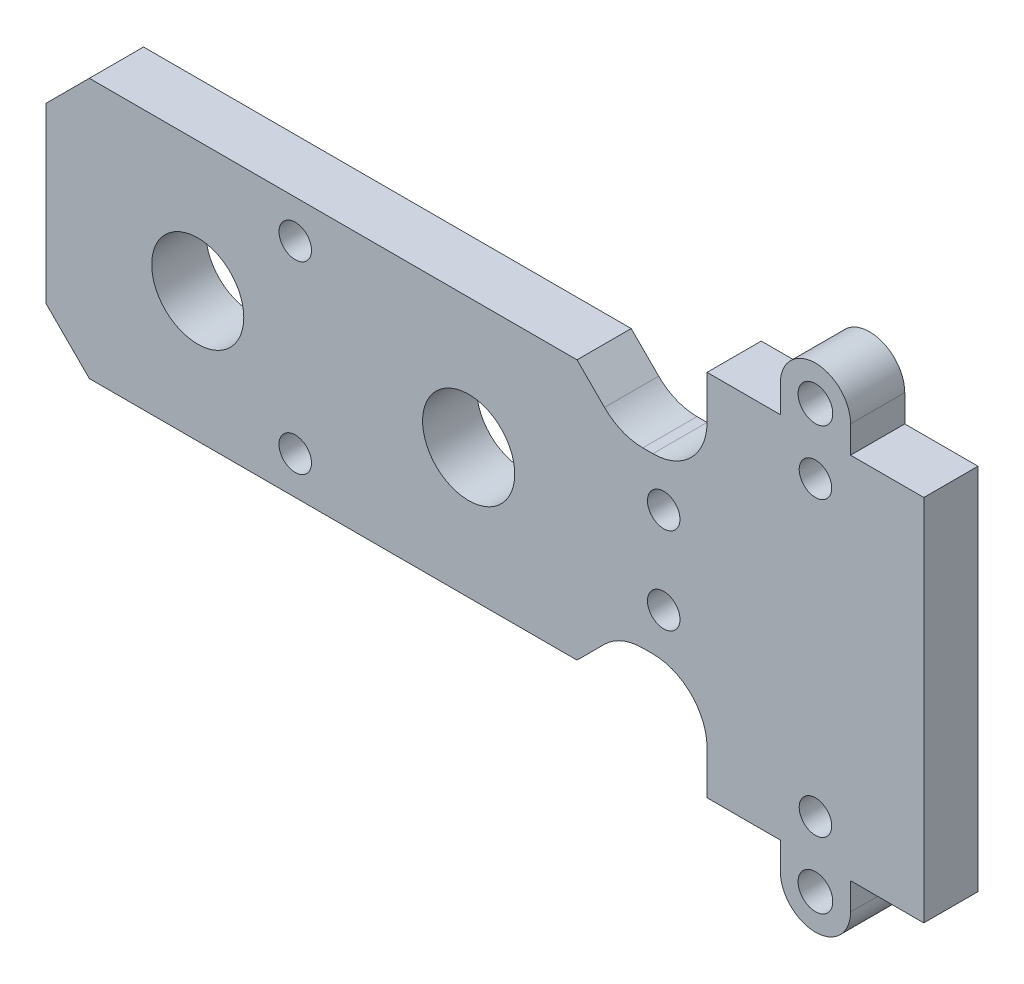
SolidWorks part; units mm, degrees
ref_plane "Plan de face" through (0, 0, 0) normal (0, 0, 1) x (1, 0, 0)
ref_plane "Plan de dessus" through (0, 0, 0) normal (0, 1, 0) x (1, 0, 0)
ref_plane "Plan de droite" through (0, 0, 0) normal (1, 0, 0) x (0, 0, -1)
sketch "Esquisse1" plane through (0, 0, 0) normal (0, 0, 1) x (1, 0, 0)
  line L0 (30.5, 0) -> (30.5, 3)
  line L1 (25.5, 8) -> (22.5, 8)
  line L2 (22.5, 8) -> (18.5, 12)
  line L3 (18.5, 12) -> (-26.5, 12)
  line L4 (-26.5, 12) -> (-30.5, 8)
  line L5 (-30.5, 8) -> (-30.5, 0)
  line L6 (22.5, -8) -> (25.5, -8)
  line L7 (30.5, -3) -> (30.5, 0)
  line L8 (-30.5, 0) -> (-30.5, -8)
  line L9 (-30.5, -8) -> (-26.5, -12)
  line L10 (-26.5, -12) -> (18.5, -12)
  line L11 (18.5, -12) -> (22.5, -8)
  arc A0 (30.5, 3) -> (25.5, 8) centre (25.5, 3) ccw
  arc A1 (25.5, -8) -> (30.5, -3) centre (25.5, -3) ccw
  circle A2 centre (-16.5, 0) radius 4.25
  circle A3 centre (-7.5, -8.5) radius 1.5
  circle A4 centre (8.5, 0) radius 4.25
  circle A5 centre (-7.5, 8.5) radius 1.5
  circle A6 centre (26.5, 4) radius 1.5
  circle A7 centre (26.5, -4) radius 1.5
extrude "Boss.-Extru.1" add sketch "Esquisse1" along normal blind 5
sketch "Esquisse2" plane through (0, 0, 0) normal (0, 0, -1) x (-1, 0, 0)
  line L0 (-30.5, -3) -> (-30.5, 3) construction
  line L2 (-30.5, 17) -> (-30.5, 8)
  line L4 (-50.5, 17) -> (-50.5, -17)
  line L5 (-30.5, -3) -> (-30.5, 3)
  line L8 (-25.5, 8) -> (-30.5, 8)
  line L10 (-30.5, -8) -> (-25.5, -8)
  line L13 (-30.5, -8) -> (-30.5, -16)
  line L19 (-30.5, 17) -> (-36.2574, 17)
  line L21 (-36.2574, 21) -> (-36.2574, 17)
  line L22 (-44.7426, 21) -> (-44.7426, 17)
  line L23 (-36.2574, -21) -> (-36.2574, -17)
  line L24 (-44.7426, -21) -> (-44.7426, -17)
  line L25 (-44.7426, 17) -> (-50.5, 17)
  line L26 (-44.7426, -17) -> (-50.5, -17)
  line L27 (-36.2574, -17) -> (-30.5, -17)
  line L28 (-30.5, -17) -> (-30.5, -16)
  circle A0 centre (-40.5, 13.5) radius 1.5
  circle A1 centre (-40.5, -13.5) radius 1.5
  circle A2 centre (-40.5, 19.5) radius 1.6
  circle A3 centre (-40.5, -19.5) radius 1.6
  arc A4 (-36.2574, 21) -> (-44.7426, 21) centre (-40.5, 19.5) ccw
  arc A5 (-44.7426, -21) -> (-36.2574, -21) centre (-40.5, -19.5) ccw
  arc A6 (-30.5, -3) -> (-25.5, -8) centre (-25.5, -3) ccw construction
  arc A7 (-25.5, 8) -> (-30.5, 3) centre (-25.5, 3) ccw construction
  arc A8 (-30.5, -3) -> (-25.5, -8) centre (-25.5, -3) ccw
  arc A9 (-25.5, 8) -> (-30.5, 3) centre (-25.5, 3) ccw
  dimension "D2" = 3
  dimension "D3" = 3
  dimension "D4" = 27
  dimension "D7" = 10
  dimension "D10" = 3.2
  dimension "D11" = 3.2
  dimension "D14" = 9
  dimension "D15" = 9
  dimension "D13" = 2.5
  dimension "D5" = 3.2
  dimension "D6" = 10
  dimension "D17" = 4
  dimension "D18" = 4
extrude "Boss.-Extru.2" add sketch "Esquisse2" against normal blind 5
fillet "Congé1" radius 1 1 edges at (44.7426, -21, 2.5)
sketch "Esquisse5" plane through (0, 0, 5) normal (0, 0, 1) x (1, 0, 0)
  line L0 (37.2574, 17) -> (37.2574, 19.5)
  line L2 (43.7426, -19.5) -> (43.7426, -17)
  line L3 (44.7426, -17) -> (44.7426, -20.8173) construction
  line L5 (37.2574, -31.95) -> (43.7426, -31.95)
  line L9 (37.2574, -17) -> (34.8491, -17)
  line L10 (36.2574, -17) -> (30.5, -17) construction
  line L11 (34.8491, -17) -> (37.2574, -31.95)
  line L12 (43.7426, -17) -> (44.7426, -17)
  line L13 (44.7426, -17) -> (44.7426, -31.95)
  line L14 (44.7426, -31.95) -> (43.7426, -31.95)
  line L15 (36.2574, 17) -> (37.2574, 17)
  line L16 (36.2574, 17) -> (36.2574, 27.9145)
  line L17 (36.2574, 27.9145) -> (46.7021, 27.9145)
  line L18 (46.7021, 27.9145) -> (46.7021, 17)
  line L19 (44.7426, 17) -> (50.5, 17) construction
  line L20 (46.7021, 17) -> (43.7426, 17)
  line L21 (43.7426, 17) -> (43.7426, 19.5)
  line L22 (37.2574, -17) -> (37.2574, -19.5)
  arc A0 (37.2574, -19.5) -> (43.7426, -19.5) centre (40.5, -19.5) ccw
  arc A1 (43.7426, 19.5) -> (37.2574, 19.5) centre (40.5, 19.5) ccw
  dimension "D1" = 1
extrude "Enlèv. mat.-Extru.1" cut sketch "Esquisse5" against normal blind 10.5
fillet "Congé2" radius 5 4 edges at (30.5, 8, 2.5) (22.5, 8, 2.5) (22.5, -8, 2.5) (30.5, -8, 2.5)
